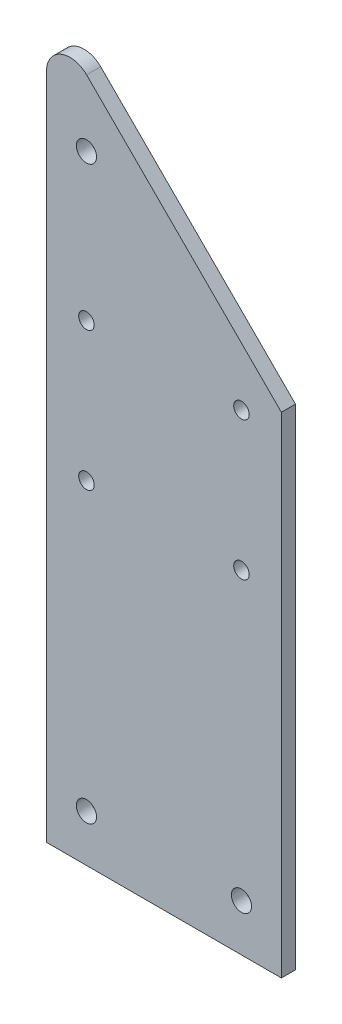
SolidWorks part; units mm, degrees
material "Thornel Mat VMA"
ref_plane "前视基准面" through (0, 0, 0) normal (0, 0, 1) x (1, 0, 0)
ref_plane "上视基准面" through (0, 0, 0) normal (0, 1, 0) x (1, 0, 0)
ref_plane "右视基准面" through (0, 0, 0) normal (1, 0, 0) x (0, 0, -1)
sketch "草图1" plane through (0, 0, 0) normal (0, 0, 1) x (1, 0, 0)
  line L0 (0, 0) -> (0, 154.3)
  line L1 (0, 154.3) -> (50, 104.3)
  line L2 (50, 104.3) -> (50, 0)
  line L3 (50, 0) -> (0, 0)
  dimension "D1" = 50
  dimension "D2" = 45
  dimension "D3" = 104.3
extrude "凸台-拉伸1" add sketch "草图1" along normal blind 3
sketch "草图2" plane through (0, 0, 3) normal (0, 0, 1) x (1, 0, 0)
  line L0 (0, 10) -> (50, 10) construction
  line L1 (0, 154.3) -> (0, 0) construction
  line L2 (50, 0) -> (50, 104.3) construction
  line L3 (50, 90.1579) -> (0, 140.1579) construction
  line L4 (50, 104.3) -> (0, 154.3) construction
  line L5 (0, 0) -> (50, 0) construction
  line L6 (8.5, 10) -> (8.5, 131.6579) construction
  line L7 (41.5, 98.6579) -> (41.5, 10) construction
  circle A0 centre (8.5, 10) radius 2.15
  circle A1 centre (41.5, 10) radius 2.15
  circle A3 centre (8.5, 131.6579) radius 2.15
  circle A4 centre (8.5, 100.45) radius 1.65
  circle A5 centre (8.5, 70.95) radius 1.65
  circle A6 centre (41.5, 70.95) radius 1.65
  circle A7 centre (41.5, 100.45) radius 1.65
  dimension "D3" = 4.3
  dimension "D4" = 8.5
  dimension "D5" = 8.5
  dimension "D6" = 70.95
  dimension "D7" = 29.5
  dimension "D8" = 3.3
  dimension "D1" = 10
  dimension "D2" = 10
extrude "切除-拉伸1" cut sketch "草图2" against normal blind 3
fillet "圆角1" radius 5 1 edges at (0, 154.3, 1.5)
